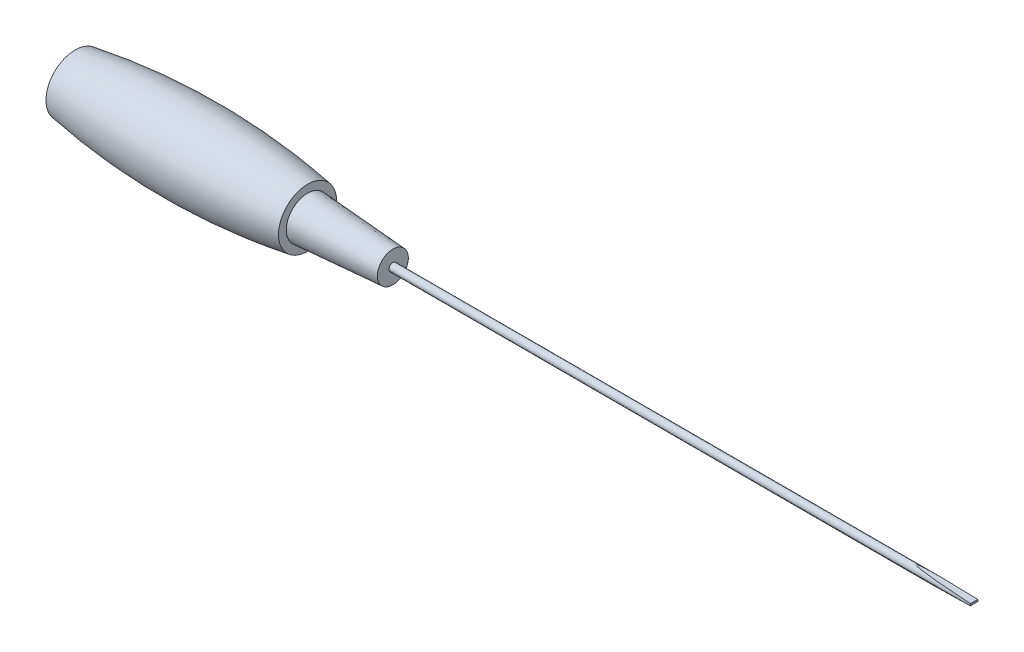
SolidWorks part; units mm, degrees
ref_plane "정면" through (0, 0, 0) normal (0, 0, 1) x (1, 0, 0)
ref_plane "윗면" through (0, 0, 0) normal (0, 1, 0) x (1, 0, 0)
ref_plane "우측면" through (0, 0, 0) normal (1, 0, 0) x (0, 0, -1)
sketch "스케치2" plane through (0, 0, 0) normal (0, 0, 1) x (1, 0, 0)
  line L0 (-74.6383, -15.0586) -> (310.6337, -15.0586) construction
  line L3 (26.9215, -7.5586) -> (26.9215, -9.5586)
  line L4 (26.9215, -9.5586) -> (48.9215, -11.0586)
  line L5 (48.9215, -11.0586) -> (48.9215, -15.0586)
  line L6 (48.9215, -15.0586) -> (-33.0785, -15.0586)
  line L7 (-33.0785, -15.0586) -> (-35.0785, -15.0586)
  line L8 (-33.0785, -7.5586) -> (-33.0785, -9.5586)
  arc A0 (-33.0785, -7.5586) -> (26.9215, -7.5586) centre (-3.0785, -190.11) cw
  arc A1 (-35.0785, -15.0586) -> (-33.0785, -9.5586) centre (-27.0811, -14.8531) cw
  point P12 (0, 0)
  dimension "D1" = 60
  dimension "D7" = 185
  dimension "D8" = 8
  dimension "D2" = 22
  dimension "D3" = 2
  dimension "D4" = 15
  dimension "D5" = 11
  dimension "D6" = 8
revolve "회전2" add sketch "스케치2" angle 360 about L0
sketch "스케치3" plane through (48.9215, 0, 0) normal (1, 0, 0) x (0, 0, -1)
  circle A0 centre (0, -15.0586) radius 1
extrude "보스-돌출1" add sketch "스케치3" along normal blind 150
sketch "스케치5" plane through (0, 0, 0) normal (0, 0, 1) x (1, 0, 0)
  line L1 (198.9215, -14.0586) -> (183.9215, -14.0586)
  line L5 (183.9215, -14.0586) -> (198.9215, -14.8086)
  line L7 (198.9215, -14.0586) -> (198.9215, -14.8086)
  line L10 (198.9215, -16.0586) -> (198.9215, -14.0586) construction
  line L11 (198.9215, -15.3086) -> (198.9215, -16.0586)
  line L12 (198.9215, -15.3086) -> (183.9215, -16.0586)
  line L13 (48.9215, -16.0586) -> (198.9215, -16.0586) construction
  line L14 (198.9215, -16.0586) -> (183.9215, -16.0586)
  dimension "D1" = 0.75
  dimension "D2" = 0.75
extrude "컷-돌출2" cut sketch "스케치5" against normal through all both and the other way through all contours L5 L1 L7 | L14 L12 L11
